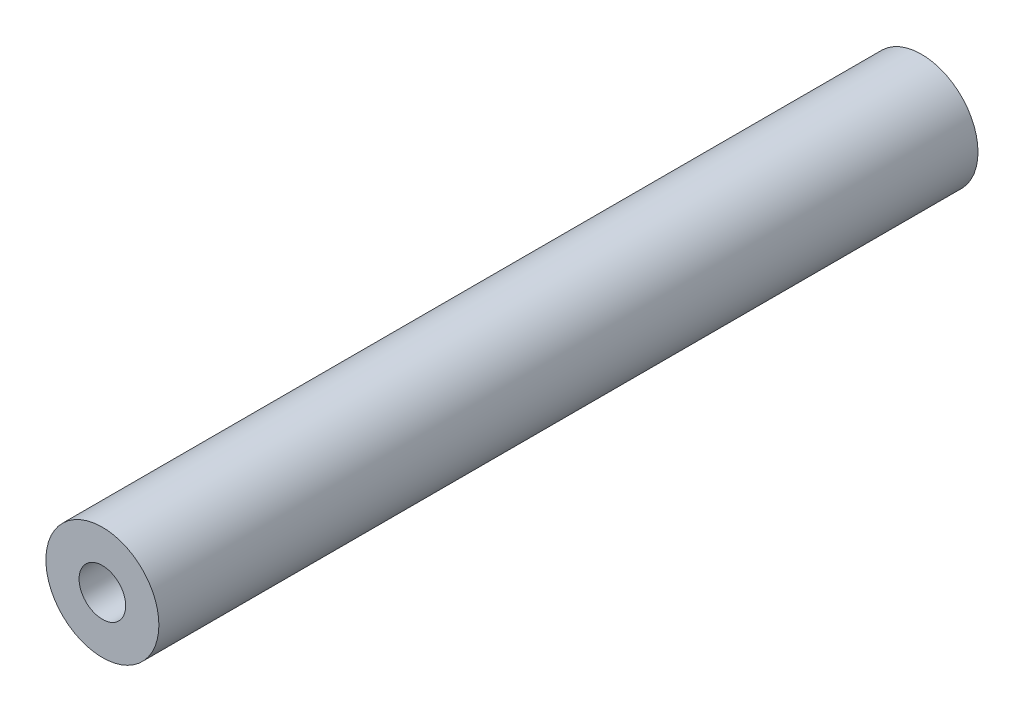
SolidWorks part; units mm, degrees
ref_plane "Plan de face" through (0, 0, 0) normal (0, 0, 1) x (1, 0, 0)
ref_plane "Plan de dessus" through (0, 0, 0) normal (0, 1, 0) x (1, 0, 0)
ref_plane "Plan de droite" through (0, 0, 0) normal (1, 0, 0) x (0, 0, -1)
sketch "Esquisse1" plane through (0, 0, 0) normal (0, 1, 0) x (1, 0, 0)
  line L0 (1.65, -17.4) -> (0, -17.4)
  line L1 (0, -17.4) -> (0, -40.6)
  line L2 (0, -40.6) -> (1.65, -40.6)
  line L3 (1.65, -40.6) -> (1.65, -58)
  line L4 (1.65, -58) -> (4, -58)
  line L5 (4, -58) -> (4, 0)
  line L6 (4, 0) -> (1.65, 0)
  line L7 (1.65, 0) -> (1.65, -17.4)
  line L8 (0, 0) -> (0, -58) construction
  dimension "D1" = 58
  dimension "D2" = 4
  dimension "D3" = 1.65
revolve "Révolution1" add sketch "Esquisse1" angle 360 about L8
